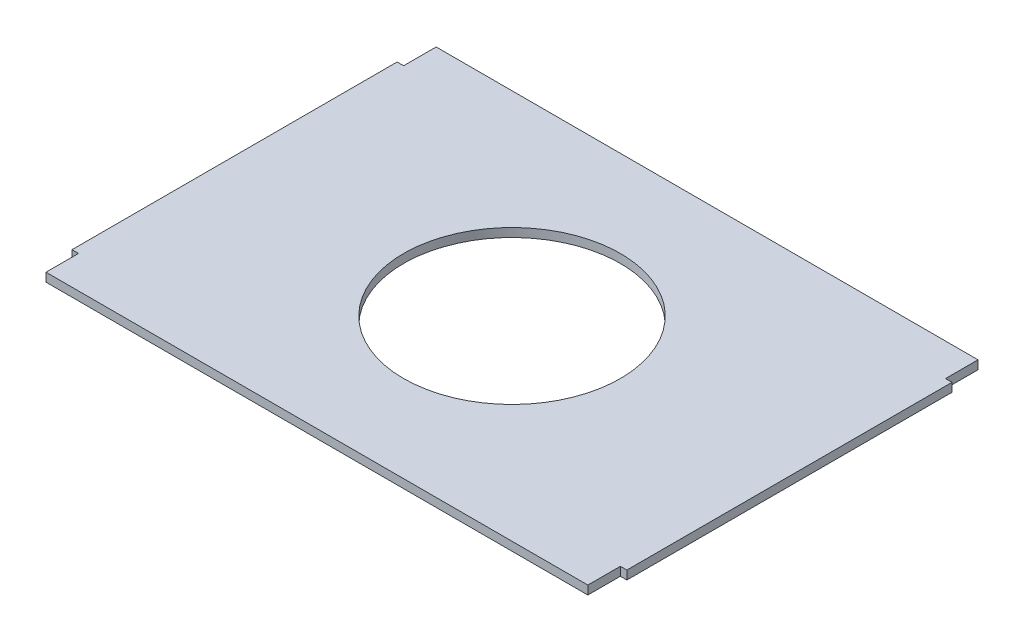
SolidWorks part; units mm, degrees
ref_plane "前视基准面" through (0, 0, 0) normal (0, 0, 1) x (1, 0, 0)
ref_plane "上视基准面" through (0, 0, 0) normal (0, 1, 0) x (1, 0, 0)
ref_plane "右视基准面" through (0, 0, 0) normal (1, 0, 0) x (0, 0, -1)
other "Configuration Table"
sketch "草图4" plane through (0, 0, 0) normal (0, 1, 0) x (1, 0, 0)
  line L0 (-125, 75) -> (-125, 90)
  line L1 (-125, -90) -> (125, -90)
  line L2 (-125, -90) -> (-125, -75)
  line L3 (-125, 90) -> (125, 90)
  line L4 (125, -90) -> (125, -75)
  line L5 (-125, -90) -> (125, 90) construction
  line L6 (-125, 90) -> (125, -90) construction
  line L7 (-128, -75) -> (-125, -75)
  line L8 (-128, -75) -> (-128, 75)
  line L9 (-128, 75) -> (-125, 75)
  line L10 (128, -75) -> (128, 75)
  line L11 (-128, -75) -> (128, 75) construction
  line L12 (-128, 75) -> (128, -75) construction
  line L13 (125, 75) -> (125, 90)
  line L14 (125, -75) -> (128, -75)
  line L15 (125, 75) -> (128, 75)
  circle A0 centre (0, 0) radius 50
  dimension "D3" = 100
  dimension "D1" = 250
  dimension "D2" = 180
  dimension "D4" = 256
  dimension "D5" = 150
extrude "凸台-拉伸3" add sketch "草图4" along normal blind 4
